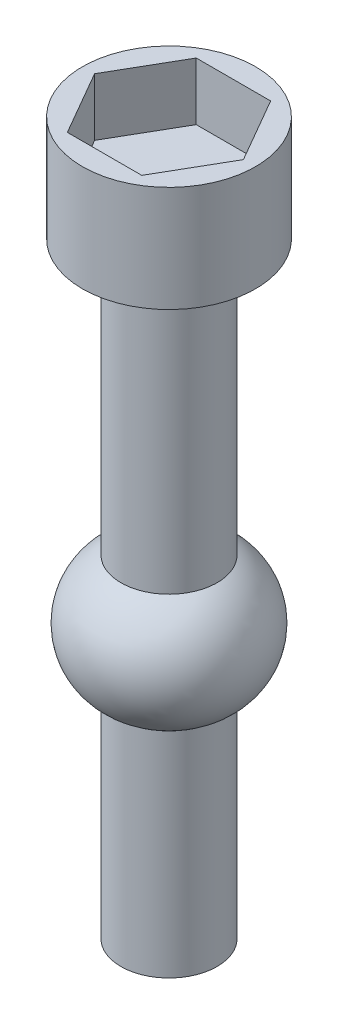
SolidWorks part; units mm, degrees
ref_plane "Front Plane" through (0, 0, 0) normal (0, 0, 1) x (1, 0, 0)
ref_plane "Top Plane" through (0, 0, 0) normal (0, 1, 0) x (1, 0, 0)
ref_plane "Right Plane" through (0, 0, 0) normal (1, 0, 0) x (0, 0, -1)
sketch "Sketch1" plane through (0, 0, 0) normal (0, 1, 0) x (1, 0, 0)
  circle A0 centre (0, 0) radius 1.25
  dimension "D1" = 2.5
extrude "Boss-Extrude1" add sketch "Sketch1" along normal blind 18.5
sketch "Sketch2" plane through (0, 18.5, 0) normal (0, 1, 0) x (1, 0, 0)
  circle A0 centre (0, 0) radius 2.25
  dimension "D1" = 4.5
extrude "Boss-Extrude2" add sketch "Sketch2" against normal blind 2.75
sketch "Sketch4" plane through (0, 0, 0) normal (0, 0, 1) x (1, 0, 0)
  line L0 (1.25, 8.6366) -> (1.25, 5.5769)
  line L1 (1.25, 0) -> (1.25, 15.75) construction
  line L2 (0, 0) -> (0, 3.6925) construction
  arc A0 (1.25, 8.6366) -> (1.25, 5.5769) centre (0.4349, 7.1067) cw
revolve "Revolve1" add sketch "Sketch4" angle 360 about L2
ref_point "Point1"
sketch "Sketch5" plane through (0, 18.5, 0) normal (0, 1, 0) x (1, 0, 0)
  line L1 (0.9667, 1.6743) -> (-0.9667, 1.6743)
  line L2 (-0.9667, 1.6743) -> (-1.9333, 0)
  line L3 (-1.9333, 0) -> (-0.9667, -1.6743)
  line L4 (-0.9667, -1.6743) -> (0.9667, -1.6743)
  line L5 (0.9667, -1.6743) -> (1.9333, 0)
  line L6 (1.9333, 0) -> (0.9667, 1.6743)
  circle A0 centre (0, 0) radius 1.6743 construction
extrude "Cut-Extrude1" cut sketch "Sketch5" against normal blind 1.5
